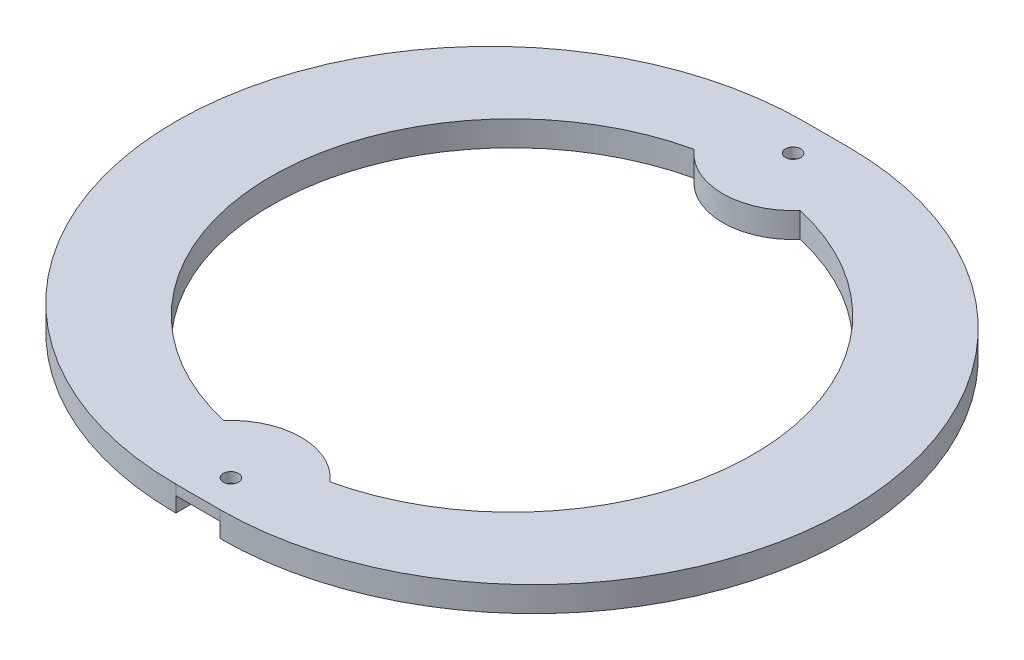
SolidWorks part; units mm, degrees
ref_plane "Front Plane" through (0, 0, 0) normal (0, 0, 1) x (1, 0, 0)
ref_plane "Top Plane" through (0, 0, 0) normal (0, 1, 0) x (1, 0, 0)
ref_plane "Right Plane" through (0, 0, 0) normal (1, 0, 0) x (0, 0, -1)
sketch "ShuttleBaseLayout" plane through (-0.0781, 0, 0) normal (0, 0, 1) x (1, 0, 0)
  line L0 (-2.1219, -0.3457) -> (-2.1219, 2.5883) construction
  line L1 (0.0781, 0) -> (-2.1219, 0)
  line L7 (-2.1219, 0) -> (-2.1219, 5)
  line L8 (-2.1219, 5) -> (-6.8398, 11.1485)
  line L9 (-6.8398, 11.1485) -> (-12.195, 7.0393)
  line L11 (-12.195, 7.0393) -> (-21.3264, 18.9396)
  line L16 (-10.2192, 15.5526) -> (13.0071, -14.7165) construction
  line L17 (0.0781, 0) -> (0.0781, 12.15)
  dimension "D5" = 37.5
  dimension "D7" = 15
  dimension "D1" = 2.2
  dimension "D2" = 5
  dimension "D3" = 7.75
  dimension "D4" = 6.75
  dimension "D6" = 12.15
sketch "Sketch88" plane through (50.0743, 0, 0) normal (0, 0, 1) x (1, 0, 0)
  line L0 (-82.2979, 33.0393) -> (-59.278, 3.0393)
  line L1 (-59.278, 3.0393) -> (-60.5385, 3.0393)
  line L2 (-60.5385, 3.0393) -> (-83.5583, 33.0393)
  line L4 (-62.3473, 7.0393) -> (-71.4788, 18.9396) construction
  line L9 (-82.2979, 33.0393) -> (-83.5583, 33.0393)
  dimension "D2" = 30
  dimension "D1" = 1
  dimension "D3" = 4
ref_plane "Plane1" through (0, 33.0393, 0) normal (0, 1, 0) x (1, 0, 0)
sketch "Sketch89" plane through (0, 33.0393, 0) normal (0, 1, 0) x (1, 0, 0)
  line L0 (-2.2, 0) -> (-2.2, 31.284) construction
  line L1 (-2.2, 0) -> (-2.2, -31.284) construction
  line L2 (-2.2, 31.284) -> (2.2, 31.284)
  line L3 (-2.2, -31.284) -> (2.2, -31.284)
  line L4 (2.2, 31.284) -> (2.2, -31.284) construction
  line L5 (0, 0) -> (0, 28) construction
  line L6 (0, 0) -> (0, -28) construction
  arc A0 (-2.2, 31.284) -> (-2.2, -31.284) centre (-2.2, 0) ccw
  arc A1 (2.2, 31.284) -> (2.2, -31.284) centre (2.2, 0) cw
  circle A2 centre (0, 0) radius 24 construction
  circle A3 centre (0, 28) radius 0.76
  circle A4 centre (0, -28) radius 0.76
  arc A5 (-5.2857, 23.4107) -> (5.2857, 23.4107) centre (0, 28) ccw
  arc A6 (-5.2857, -23.4107) -> (5.2857, -23.4107) centre (0, -28) cw
  arc A7 (-5.2857, 23.4107) -> (-5.2857, -23.4107) centre (0, 0) ccw
  arc A8 (5.2857, 23.4107) -> (5.2857, -23.4107) centre (0, 0) cw
  point P0 (-2.2, 0)
  point P1 (0, 0)
  point P21 (0, 24.661)
  point P22 (0, 28.3375)
  point P23 (0, 0)
  point P24 (0, 0)
  dimension "D2" = 48
  dimension "D4" = 1.52
  dimension "D5" = 7
  dimension "D1" = 4.4
  dimension "D3" = 28
extrude "Boss-Extrude1" add sketch "Sketch89" along normal blind 2.5
sketch "Sketch91" plane through (0, 33.0393, 0) normal (0, -1, 0) x (1, 0, 0)
  line L0 (2.2, -31.284) -> (2.2, 31.284) construction
  line L5 (-2.2, 31.284) -> (2.2, 31.284)
  line L6 (-2.2, 31.284) -> (-2.2, 23.784)
  line L12 (-2.2, 23.784) -> (2.2, 23.784)
  line L13 (2.2, 31.284) -> (2.2, 23.784)
  line L29 (-2.2, -31.284) -> (2.2, -31.284)
  line L30 (-2.2, -31.284) -> (-2.2, -23.784)
  line L31 (-2.2, -23.784) -> (2.2, -23.784)
  line L32 (2.2, -31.284) -> (2.2, -23.784)
  dimension "D1" = 7.5
extrude "Cut-Extrude1" cut sketch "Sketch91" against normal blind 1.5
equation "\"DriveAngle\"= 37.5"
equation "\"ThreadedRodOffset\"=1.5"
equation "\"ShuttleOffsetCenter\"= 3.5mm"
equation "\"RotationalCenterAP\"=3.6"
equation "\"RotationalCenterML\"= 2.2"
equation "\"BaseRotationAngle\"= \"RotationalSpacing\" / 2"
equation "\"HolderBottomDistanceAboveProjection\"= 5mm"
equation "\"HolderHeight\"=1.5"
equation "\"CannulaOffset\"= 2"
equation "\"BaseWidening\"=0.5"
equation "\"TetrodeCanulaDiameter\"= 1.3mm"
equation "\"StimElectrodeCanulaDiameter\"= 0.75mm"
equation "\"TapDrill0_80\"=1.19063"
equation "\"LooseTapDrill0_80\"=1.52"
equation "\"StabilizerRodHole\"=0.8128"
equation "\"RetainingSlotWidth\"=0.5"
equation "\"DriveToEIBSpace\"= 9"
equation "\"0_80_TravelDistance\"=15"
equation "\"D7@ShuttleBaseLayout\" = \"0_80_TravelDistance\""
equation "\"D5@ShuttleBaseLayout\" = \"DriveAngle\""
equation "\"StabilizerTo0_80Distance\"=2.5"
equation "\"30gaTubingSupport\"=3.5"
equation "\"23GaChannel\"=1.25"
equation "\"RotationalSpacing\"= 15"
equation "\"HalfNumberOfShuttles\"= 4"
equation "\"WeightReductionCutCenter\"= 80"
equation "\"EIB-Height\"= 15"
equation "\"19gaLength\"=7.5"
equation "\"ConeThickness\"=1"
equation "\"ConeBelowBase\"=5"
equation "\"ConeAboveRim\"= 17"
equation "\"ConeMountAboveBottomRim\"=3"
equation "\"ConeThicknessReduction\"= 0.25"
equation "\"ConeHeightBlockReduction\"=6"
equation "\"Rim\"=10"
equation "\"RimHeight\"=2.5"
equation "\"RimHeightLessOffset\"=2.5"
equation "\"D1@ShuttleBaseLayout\"=\"RotationalCenterML\""
equation "\"D3@ShuttleBaseLayout\"=7.75"
equation "\"D4@ShuttleBaseLayout\"=6.75"
equation "\"D1@Sketch88\"=\"ConeThickness\""
equation "\"D1@Sketch89\"=\"RotationalCenterML\"*2"
equation "\"D4@Sketch89\"=\"LooseTapDrill0_80\""
